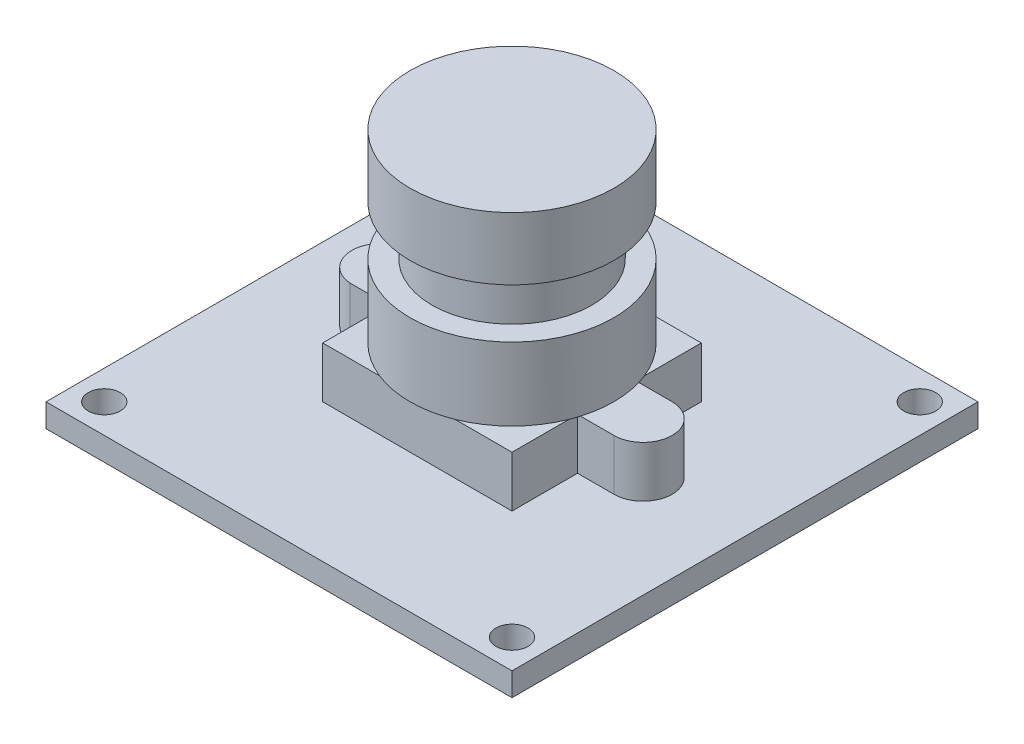
SolidWorks part; units mm, degrees
material "PE(聚乙烯)"
ref_plane "前视基准面" through (0, 0, 0) normal (0, 0, 1) x (1, 0, 0)
ref_plane "上视基准面" through (0, 0, 0) normal (0, 1, 0) x (1, 0, 0)
ref_plane "右视基准面" through (0, 0, 0) normal (1, 0, 0) x (0, 0, -1)
sketch "草图1" plane through (0, 0, 0) normal (0, 1, 0) x (1, 0, 0)
  line L1 (-16, 16) -> (16, 16)
  line L2 (-16, 16) -> (-16, -16)
  line L3 (-16, -16) -> (16, -16)
  line L4 (16, 16) -> (16, -16)
  line L5 (-16, 16) -> (16, -16) construction
  line L6 (-16, -16) -> (16, 16) construction
  point P0 (0, 0)
  dimension "D1" = 32
  dimension "D2" = 32
extrude "凸台-拉伸1" add sketch "草图1" along normal blind 1.6
hole_wizard "M2 间隙孔1" positions "草图2" profile "草图3" hole size "M2" standard "GB" end condition through all
sketch "草图2" plane through (0, 1.6, 0) normal (0, 1, 0) x (1, 0, 0)
  line L0 (-16, 16) -> (-16, -16) construction
  line L2 (16, 16) -> (-16, 16) construction
  point P0 (-14, 14)
  point P2 (14, 14)
  point P4 (14, -14)
  point P6 (-14, -14)
  dimension "D1" = 28
  dimension "D2" = 28
  dimension "D3" = 2
  dimension "D4" = 2
sketch "草图3" plane through (-14, 1.6, -14) normal (1, 0, 0) x (0, 0, 1)
  line L0 (0, 0) -> (0, 1.6)
  line L1 (0, 1.6) -> (1.1, 1.6)
  line L2 (1.1, 1.6) -> (1.1, 0)
  line L5 (1.1, 0) -> (0, 0)
  line L11 (0, -6.35) -> (0, 107.95) construction
  dimension "通孔孔直径" = 2.2
  dimension "通孔孔深度" = 1.6
sketch "草图4" plane through (0, 0, 0) normal (0, 1, 0) x (1, 0, 0)
  line L1 (-5, 15.08) -> (5, 15.08)
  line L2 (-5, 15.08) -> (-5, 10.38)
  line L3 (-5, 10.38) -> (5, 10.38)
  line L4 (5, 15.08) -> (5, 10.38)
  line L5 (0, 10.38) -> (0, 16) construction
  line L6 (16, 16) -> (-16, 16) construction
  dimension "D3" = 0.92
  dimension "D1" = 10
  dimension "D2" = 4.7
extrude "凸台-拉伸2" add sketch "草图4" against normal blind 1.7
sketch "草图6" plane through (0, 1.6, 0) normal (0, 1, 0) x (1, 0, 0)
  line L0 (-14, 14) -> (-14, -14) construction
  line L1 (-6.5, 6.5) -> (6.5, 6.5)
  line L2 (-6.5, 6.5) -> (-6.5, 2)
  line L3 (-6.5, -6.5) -> (6.5, -6.5)
  line L4 (6.5, 6.5) -> (6.5, 2)
  line L5 (-6.5, 6.5) -> (6.5, -6.5) construction
  line L6 (-6.5, -6.5) -> (6.5, 6.5) construction
  line L7 (-14, 0) -> (16, 0) construction
  line L8 (16, -16) -> (16, 16) construction
  line L9 (0, -16) -> (0, 15.08) construction
  line L10 (-9.119, 2) -> (-6.5, 2)
  line L12 (-9.119, -2) -> (-6.5, -2)
  line L14 (-6.5, -2) -> (-6.5, -6.5)
  line L15 (6.5, -2) -> (6.5, -6.5)
  line L16 (6.5, 2) -> (9, 2)
  line L18 (6.5, -2) -> (9, -2)
  line L22 (-16, -16) -> (16, -16) construction
  line L23 (5, 15.08) -> (-5, 15.08) construction
  arc A0 (-9.119, 2) -> (-9.119, -2) centre (-9, 0) ccw
  arc A1 (9, -2) -> (9, 2) centre (9, 0) ccw
  point P0 (0, 0)
  point P13 (6.5, -3.25)
  point P14 (-6.5, -3.25)
  dimension "D1" = 18
  dimension "D2" = 13
  dimension "D3" = 13
  dimension "D4" = 4
  dimension "D5" = 4
  dimension "D6" = 2
  dimension "D7" = 9
extrude "凸台-拉伸4" add sketch "草图6" along normal blind 3.5
sketch "草图7" plane through (0, 5.1, 0) normal (0, 1, 0) x (1, 0, 0)
  line L0 (0, 6.5) -> (0, -4.5367) construction
  line L1 (6.5, 6.5) -> (-6.5, 6.5) construction
  line L3 (11, 0) -> (-11.0035, 0) construction
  arc A0 (9, -2) -> (9, 2) centre (9, 0) ccw construction
  arc A1 (-9.119, 2) -> (-9.119, -2) centre (-9, 0) ccw construction
  circle A3 centre (-0.0018, 0) radius 7
  dimension "D1" = 14
extrude "凸台-拉伸5" add sketch "草图7" along normal blind 5
sketch "草图8" plane through (0, 10.1, 0) normal (0, 1, 0) x (1, 0, 0)
  circle A0 centre (0, 0) radius 5.5
  dimension "D1" = 11
extrude "凸台-拉伸6" add sketch "草图8" along normal blind 3.4
sketch "草图9" plane through (0, 13.5, 0) normal (0, 1, 0) x (1, 0, 0)
  circle A0 centre (0, 0) radius 7
  dimension "D1" = 14
extrude "凸台-拉伸7" add sketch "草图9" along normal blind 4.3
